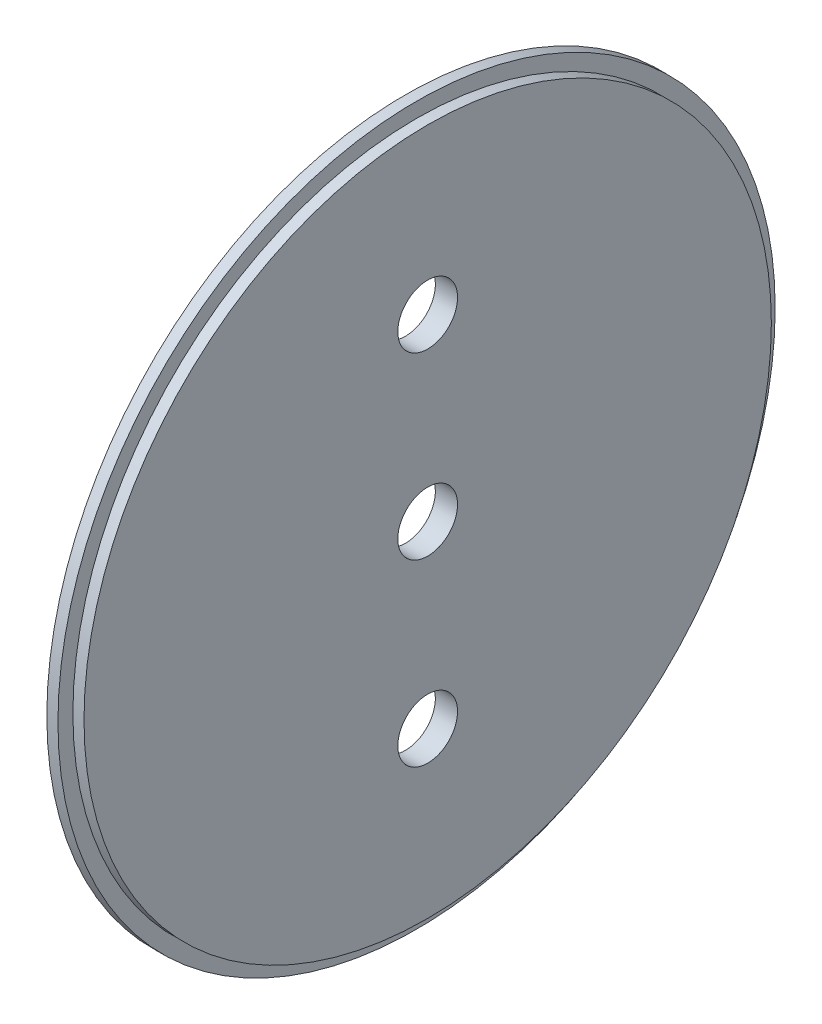
SolidWorks part; units mm, degrees
ref_plane "Front Plane" through (0, 0, 0) normal (1, 0, 0) x (0, 1, 0)
ref_plane "Top Plane" through (0, 0, 0) normal (0, 0, 1) x (0, 1, 0)
ref_plane "Right Plane" through (0, 0, 0) normal (0, 1, 0) x (-1, 0, 0)
sketch "Sketch1" plane through (0, 0, 0) normal (1, 0, 0) x (0, 1, 0)
  circle A0 centre (0, 0) radius 38.1
  dimension "D1" = 76.2
extrude "Boss-Extrude1" add sketch "Sketch1" along normal blind 1.1811
sketch "Sketch2" plane through (1.1811, 0, 0) normal (1, 0, 0) x (0, 1, 0)
  circle A0 centre (0, 0) radius 36.5125
  dimension "D1" = 73.025
extrude "Boss-Extrude2" add sketch "Sketch2" along normal blind 1.1811
sketch "Sketch3" plane through (0, 0, 0) normal (-1, 0, 0) x (0, -1, 0)
  circle A0 centre (0, 0) radius 3.175
  circle A1 centre (19.05, 0) radius 3.175
  circle A2 centre (-19.05, 0) radius 3.175
  point P7 (0, 0)
  point P8 (0, 0)
  dimension "D1" = 6.35
  dimension "D2" = 6.35
  dimension "D3" = 6.35
  dimension "D4" = 19.05
  dimension "D5" = 19.05
extrude "Cut-Extrude1" cut sketch "Sketch3" against normal through all
